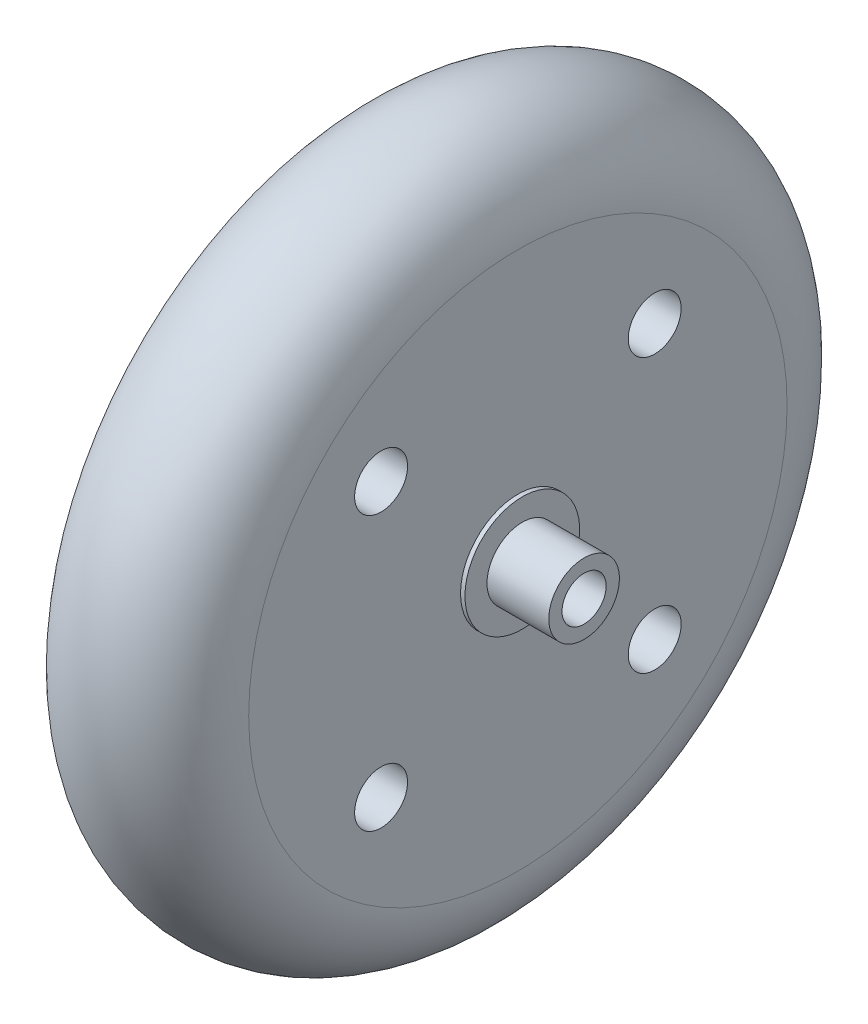
SolidWorks part; units mm, degrees
ref_plane "Front Plane" through (0, 0, 0) normal (0, 0, 1) x (1, 0, 0)
ref_plane "Top Plane" through (0, 0, 0) normal (0, 1, 0) x (1, 0, 0)
ref_plane "Right Plane" through (0, 0, 0) normal (1, 0, 0) x (0, 0, -1)
sketch "Sketch1" plane through (0, 0, 0) normal (0, 0, 1) x (1, 0, 0)
  line L0 (0, 0) -> (7.9851, 0) construction
  line L3 (0, 30) -> (0, 2.5) construction
  line L6 (20, 30) -> (20, 4) construction
  line L8 (27, 4) -> (27, 2.5)
  line L9 (0.5, 30.5) -> (0.5, 2.5)
  line L10 (19.5, 30.5) -> (19.5, 6.5)
  line L11 (0, 2.5) -> (20, 2.5) construction
  line L12 (20, 2.5) -> (27, 2.5)
  line L13 (27, 4) -> (20, 4)
  line L16 (20, 4) -> (20, 6.5)
  line L17 (20, 6.5) -> (19.5, 6.5)
  line L18 (0.5, 2.5) -> (20, 2.5)
  arc A0 (19.5, 30.5) -> (0.5, 30.5) centre (10, 30.5) ccw
  point P13 (10, 40)
  point P15 (10, 2.5)
  dimension "D3" = 19
  dimension "D1" = 2.5
  dimension "D2" = 20
  dimension "D4" = 80
  dimension "D5" = 7
  dimension "D6" = 8
  dimension "D8" = 13
revolve "Revolve1" add sketch "Sketch1" angle 360 about L0
sketch "Sketch2" plane through (19.5, 0, 0) normal (1, 0, 0) x (0, 0, -1)
  line L0 (-15.5, 15.5) -> (15.5, -15.5) construction
  line L1 (-15.5, 15.5) -> (15.5, 15.5) construction
  line L2 (-15.5, 15.5) -> (-15.5, -15.5) construction
  line L3 (-15.5, -15.5) -> (15.5, -15.5) construction
  line L4 (15.5, 15.5) -> (15.5, -15.5) construction
  line L5 (-15.5, -15.5) -> (15.5, 15.5) construction
  circle A0 centre (-15.5, 15.5) radius 3
  circle A1 centre (15.5, 15.5) radius 3
  circle A2 centre (15.5, -15.5) radius 3
  circle A3 centre (-15.5, -15.5) radius 3
  dimension "D1" = 6
  dimension "D2" = 31
extrude "Cut-Extrude1" cut sketch "Sketch2" against normal through all
